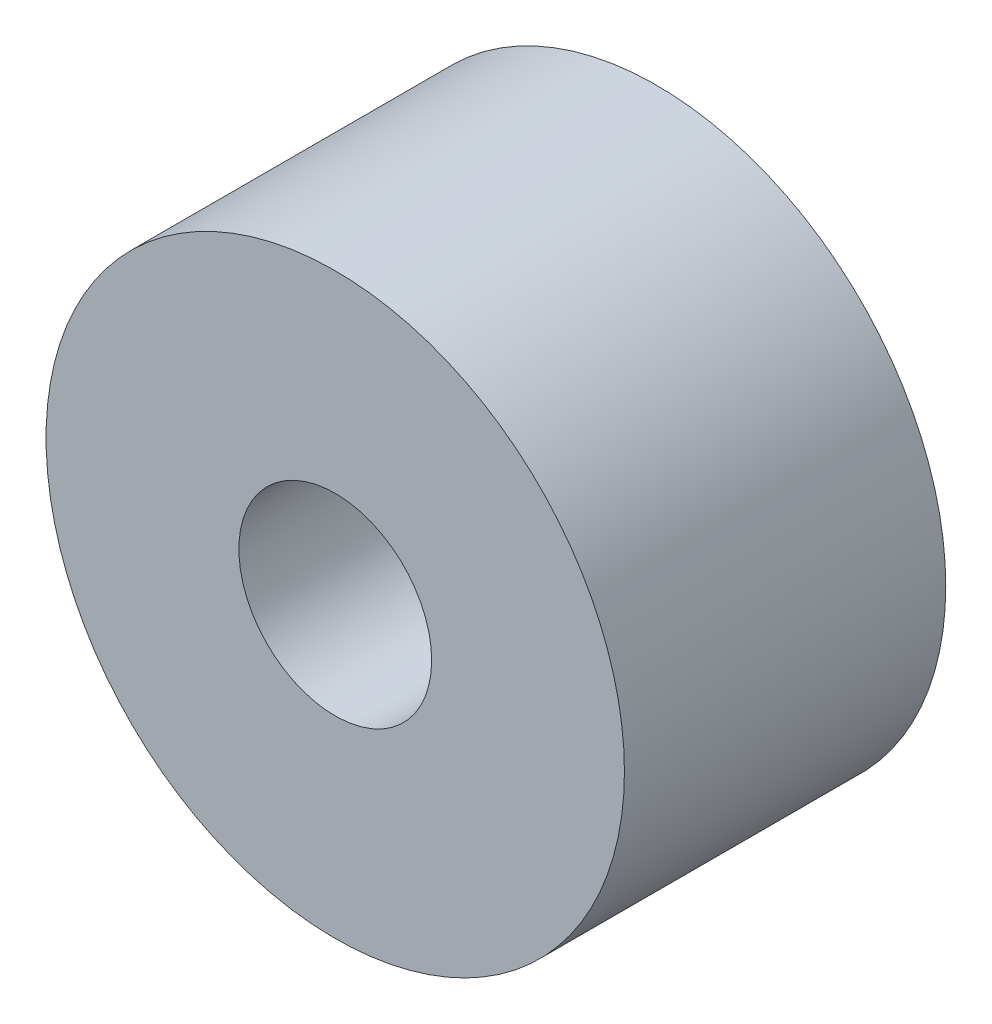
SolidWorks part; units mm, degrees
ref_plane "前视基准面" through (0, 0, 0) normal (0, 0, 1) x (1, 0, 0)
ref_plane "上视基准面" through (0, 0, 0) normal (0, 1, 0) x (1, 0, 0)
ref_plane "右视基准面" through (0, 0, 0) normal (1, 0, 0) x (0, 0, -1)
other "Configuration Table"
sketch "草图1" plane through (0, 0, 0) normal (0, 0, 1) x (1, 0, 0)
  circle A0 centre (0, 0) radius 1.5
  circle A1 centre (0, 0) radius 4.5
  dimension "D1" = 3
  dimension "D2" = 9
extrude "凸台-拉伸1" add sketch "草图1" along normal blind 5
